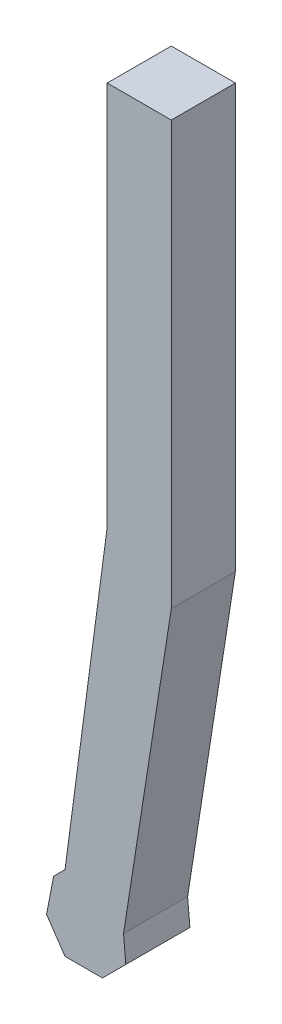
SolidWorks part; units mm, degrees
ref_plane "Front Plane" through (0, 0, 0) normal (0, 0, 1) x (1, 0, 0)
ref_plane "Top Plane" through (0, 0, 0) normal (0, 1, 0) x (1, 0, 0)
ref_plane "Right Plane" through (0, 0, 0) normal (1, 0, 0) x (0, 0, -1)
sketch "Sketch9" plane through (0, 0, 0) normal (0, 0, 1) x (1, 0, 0)
  line L1 (1.0845, 39.4262) -> (6.0845, 39.4262)
  line L2 (1.0845, 39.4262) -> (1.0845, 9.4262)
  line L4 (6.0845, 39.4262) -> (6.0845, 6.4262)
  line L5 (-3.0965, -16.2481) -> (-3.6423, -19.1026)
  line L6 (-3.6423, -19.1026) -> (-2.2048, -21.2197)
  line L7 (1.0845, 9.4262) -> (-2.2048, -15.3564)
  line L8 (6.0845, 6.4262) -> (2.3578, -17.4015)
  line L10 (-2.2048, -15.3564) -> (-3.0965, -16.2481)
  line L11 (-2.2048, -21.2197) -> (0.7121, -21.2197)
  line L12 (0.7121, -21.2197) -> (2.5356, -19.3962)
  line L13 (2.5356, -19.3962) -> (2.3578, -17.4015)
  point P0 (0, 0)
  dimension "D1" = 30
  dimension "D2" = 33
  dimension "D3" = 25
  dimension "D4" = 5
extrude "Boss-Extrude2" add sketch "Sketch9" along normal blind 5
sketch "Sketch11" plane through (0, 0, 5) normal (0, 0, 1) x (1, 0, 0)
  circle A1 centre (3.5488, 35.9074) radius 1.5
